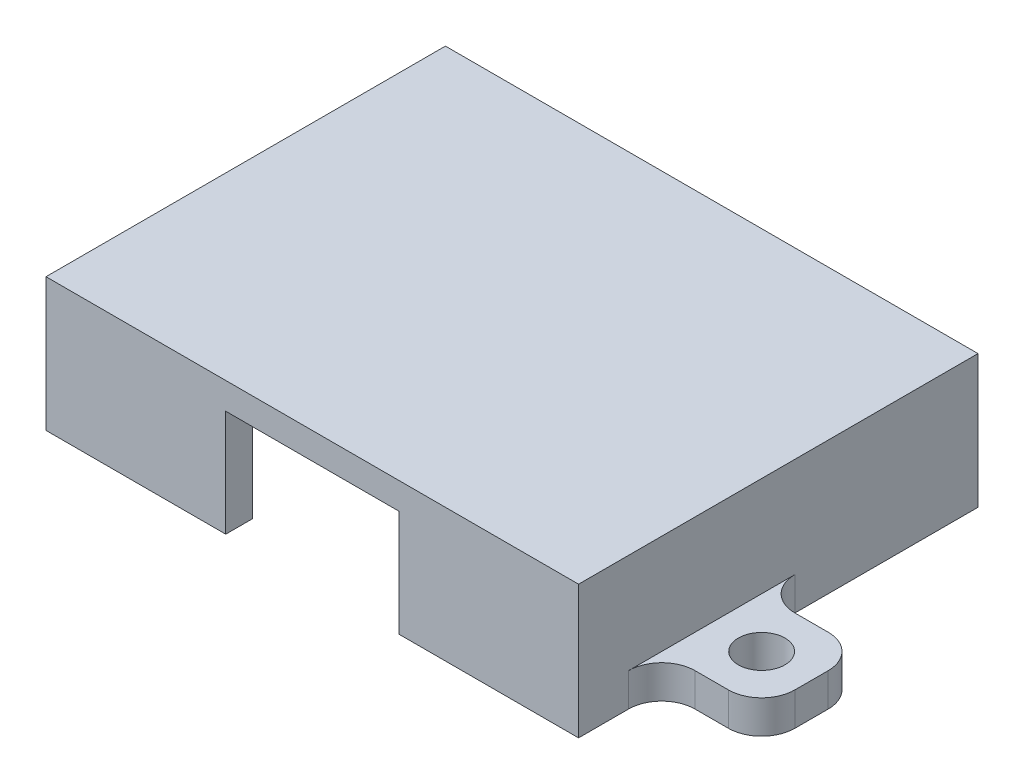
SolidWorks part; units mm, degrees
ref_plane "Front Plane" through (0, 0, 0) normal (0, 0, 1) x (1, 0, 0)
ref_plane "Top Plane" through (0, 0, 0) normal (0, 1, 0) x (1, 0, 0)
ref_plane "Right Plane" through (0, 0, 0) normal (1, 0, 0) x (0, 0, -1)
sketch "Sketch1" plane through (0, 0, 0) normal (0, 1, 0) x (1, 0, 0)
  line L1 (0, 0) -> (40, 0)
  line L2 (0, 0) -> (0, 30)
  line L3 (0, 30) -> (40, 30)
  line L4 (40, 0) -> (40, 30)
  dimension "D1" = 40
  dimension "D2" = 30
extrude "Boss-Extrude1" add sketch "Sketch1" along normal blind 10
sketch "Sketch2" plane through (0, 0, 0) normal (0, -1, 0) x (1, 0, 0)
  line L0 (13.5, 0) -> (26.5, 0)
  line L1 (0, 0) -> (40, 0) construction
  line L2 (26.5, 0) -> (26.5, -2)
  line L3 (26.5, -2) -> (38, -2)
  line L4 (38, -2) -> (38, -28)
  line L6 (2, -28) -> (2, -2)
  line L7 (2, -2) -> (13.5, -2)
  line L8 (13.5, -2) -> (13.5, 0)
  line L9 (40, 0) -> (40, -30) construction
  line L10 (0, -30) -> (0, 0) construction
  line L11 (40, -30) -> (0, -30) construction
  line L12 (2, -28) -> (2, -30)
  line L13 (2, -30) -> (8, -30)
  line L14 (8, -30) -> (8, -28)
  line L15 (8, -28) -> (32, -28)
  line L16 (32, -28) -> (32, -30)
  line L17 (32, -30) -> (38, -30)
  line L18 (38, -30) -> (38, -28)
  point P16 (20, 0)
  point P17 (20, -30)
  dimension "D1" = 13
  dimension "D2" = 2
  dimension "D3" = 2
  dimension "D4" = 2
  dimension "D5" = 2
  dimension "D6" = 6
extrude "Cut-Extrude1" cut sketch "Sketch2" against normal offset from surface (8 mm away) 2 up to face at (20, 10, -15)
sketch "Sketch3" plane through (0, 0, 0) normal (-1, 0, 0) x (0, 0, 1)
  line L0 (-30, 0) -> (0, 0) construction
  line L1 (-6.25, 0) -> (-13.75, 0)
  line L2 (-6.25, 0) -> (-6.25, 2.5)
  line L3 (-6.25, 2.5) -> (-13.75, 2.5)
  line L4 (-13.75, 0) -> (-13.75, 2.5)
  line L5 (0, 10) -> (0, 0) construction
  point P6 (-10, 2.5)
  dimension "D1" = 7.5
  dimension "D2" = 10
  dimension "D3" = 2.5
extrude "Boss-Extrude2" add sketch "Sketch3" along normal blind 7.5
sketch "Sketch4" plane through (0, 2.5, 0) normal (0, 1, 0) x (1, 0, 0)
  line L0 (-7.5, 13.75) -> (0, 13.75) construction
  line L1 (-7.5, 6.25) -> (-7.5, 13.75) construction
  circle A0 centre (-3.75, 10) radius 1.75
  point P2 (-3.75, 13.75)
  point P3 (-7.5, 10)
  dimension "D1" = 3.5
extrude "Cut-Extrude2" cut sketch "Sketch4" against normal through all
fillet "Fillet1" radius 2.5 4 edges at (0, 1.25, -6.25) (-7.5, 1.25, -6.25) (-7.5, 1.25, -13.75) (0, 1.25, -13.75)
ref_plane "Plane1" through (20, 0, 0) normal (-1, 0, 0) x (0, 0, 1)
mirror "Mirror1" about plane through (20, 0, 0) normal (-1, 0, 0) of "Boss-Extrude2", "Cut-Extrude2"
fillet "Fillet2" radius 2.5 4 edges at (47.5, 1.25, -13.75) (40, 1.25, -13.75) (47.5, 1.25, -6.25) (40, 1.25, -6.25)
